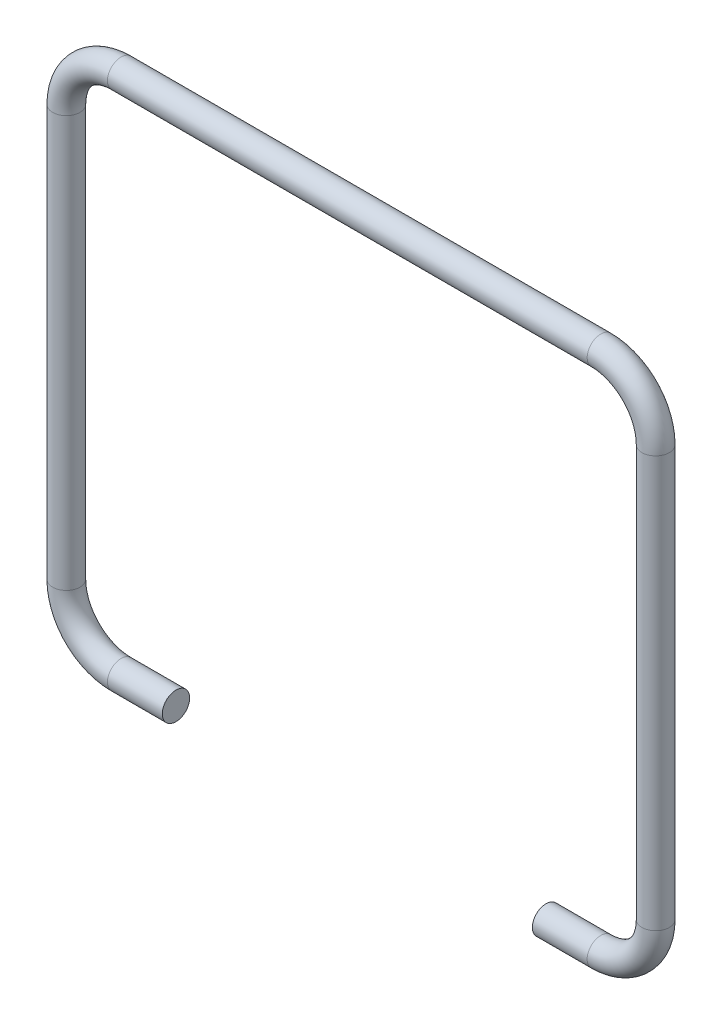
SolidWorks part; units mm, degrees
ref_plane "前视基准面" through (0, 0, 0) normal (0, 0, 1) x (1, 0, 0)
ref_plane "上视基准面" through (0, 0, 0) normal (0, 1, 0) x (1, 0, 0)
ref_plane "右视基准面" through (0, 0, 0) normal (1, 0, 0) x (0, 0, -1)
other "Configuration Table"
sketch "草图1" plane through (0, 0, 0) normal (0, 0, 1) x (1, 0, 0)
  line L0 (0, 0) -> (0, 19) construction
  line L1 (-6.75, 0) -> (-8.75, 0)
  line L2 (-10.75, 2) -> (-10.75, 17)
  line L3 (-8.75, 19) -> (8.75, 19)
  line L4 (6.75, 0) -> (8.75, 0)
  line L5 (10.75, 2) -> (10.75, 17)
  arc A0 (-10.75, 17) -> (-8.75, 19) centre (-8.75, 17) cw
  arc A1 (-8.75, 0) -> (-10.75, 2) centre (-8.75, 2) cw
  arc A2 (8.75, 0) -> (10.75, 2) centre (8.75, 2) ccw
  arc A3 (10.75, 17) -> (8.75, 19) centre (8.75, 17) ccw
  point P9 (-10.75, 19)
  point P12 (-10.75, 0)
  point P20 (0, 19)
  dimension "D4" = 2
  dimension "D5" = 2
  dimension "D1" = 10.75
  dimension "D2" = 4
  dimension "D3" = 19
sweep "扫描1" add path "草图1" circular profile diameter 1 parameters "D3"=1
